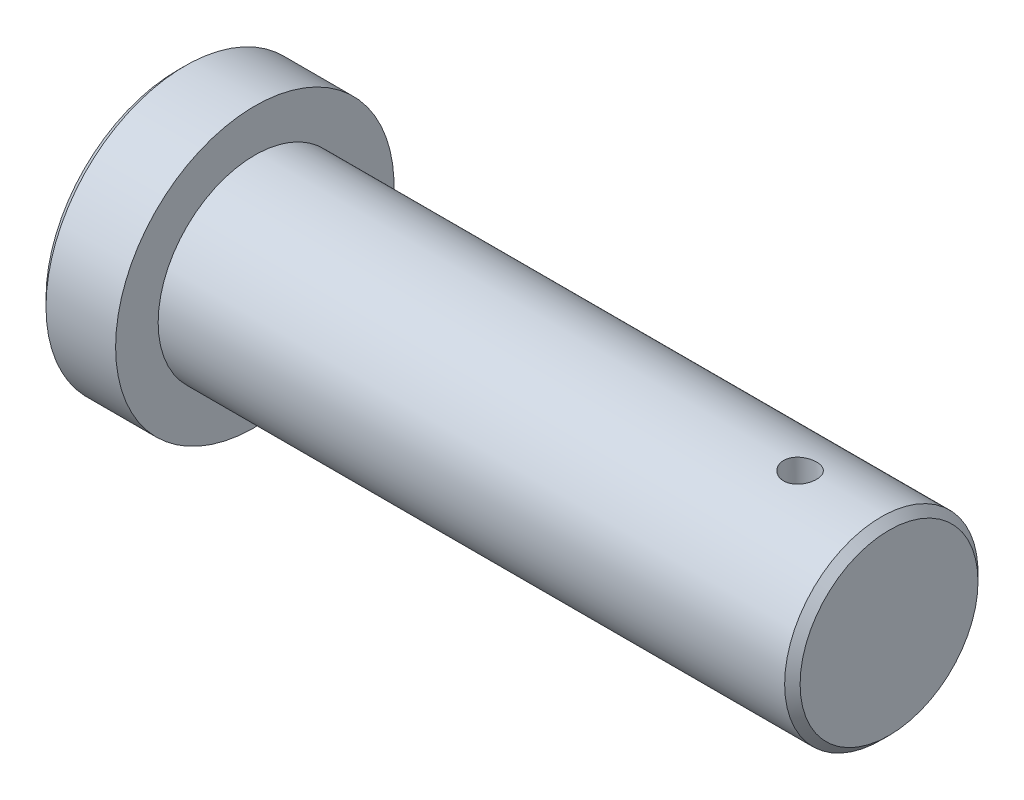
SolidWorks part; units mm, degrees
ref_plane "Front Plane" through (0, 0, 0) normal (0, 0, 1) x (1, 0, 0)
ref_plane "Top Plane" through (0, 0, 0) normal (0, 1, 0) x (1, 0, 0)
ref_plane "Right Plane" through (0, 0, 0) normal (1, 0, 0) x (0, 0, -1)
sketch "Sketch1" plane through (0, 0, 0) normal (0, 0, 1) x (1, 0, 0)
  line L0 (0, 0) -> (17351.7705, 0) construction
  line L1 (0, 0) -> (0, 18)
  line L2 (0, 18) -> (10, 18)
  line L3 (10, 18) -> (10, 12.5)
  line L4 (10, 12.5) -> (92, 12.5)
  line L5 (92, 12.5) -> (92, 0)
  line L6 (92, 0) -> (0, 0)
  dimension "D1" = 36
  dimension "D2" = 25
  dimension "D3" = 10
  dimension "D4" = 82
revolve "Revolve1" add sketch "Sketch1" angle 360 about L0
sketch "Sketch2" plane through (0, 0, 0) normal (0, 0, 1) x (1, 0, 0)
  line L0 (80.5, 12.5) -> (80.5, -12.5) construction
  line L1 (92, 12.5) -> (10, 12.5) construction
  line L2 (10, -12.5) -> (92, -12.5) construction
  line L3 (92, -12.5) -> (92, 12.5) construction
  line L4 (83, -12.5) -> (82.625, 12.5)
  line L5 (82.625, 12.5) -> (80.5, 12.5)
  line L6 (80.5, 12.5) -> (80.5, -12.5)
  line L7 (80.5, -12.5) -> (83, -12.5)
  dimension "D1" = 11.5
  dimension "D2" = 2.5
  dimension "D3" = 2.125
revolve "Cut-Revolve1" cut sketch "Sketch2" angle 360 about L0
chamfer "Chamfer1" distance 1 angle 45 2 edges at (0, 0, 18) (92, 0, 12.5)
